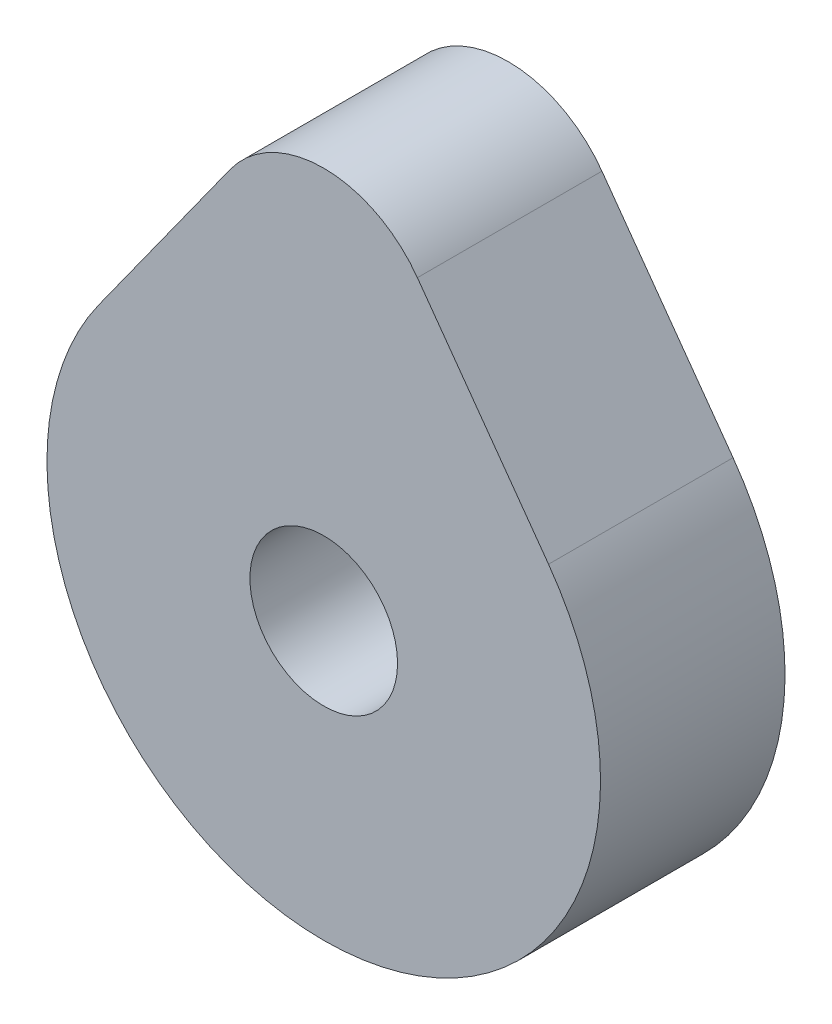
SolidWorks part; units mm, degrees
ref_plane "Front Plane" through (0, 0, 0) normal (0, 0, 1) x (1, 0, 0)
ref_plane "Top Plane" through (0, 0, 0) normal (0, 1, 0) x (1, 0, 0)
ref_plane "Right Plane" through (0, 0, 0) normal (1, 0, 0) x (0, 0, -1)
sketch "Sketch1" plane through (0, 0, 0) normal (0, 0, 1) x (1, 0, 0)
  line L0 (-12.1835, 8.75) -> (-5.0765, 18.6458)
  line L1 (12.1835, 8.75) -> (5.0765, 18.6458)
  arc A0 (-12.1835, 8.75) -> (12.1835, 8.75) centre (0, 0) ccw
  arc A1 (5.0765, 18.6458) -> (-5.0765, 18.6458) centre (0, 15) ccw
  circle A2 centre (0, 0) radius 4
  dimension "D1" = 15
extrude "Boss-Extrude1" add sketch "Sketch1" along normal blind 10
